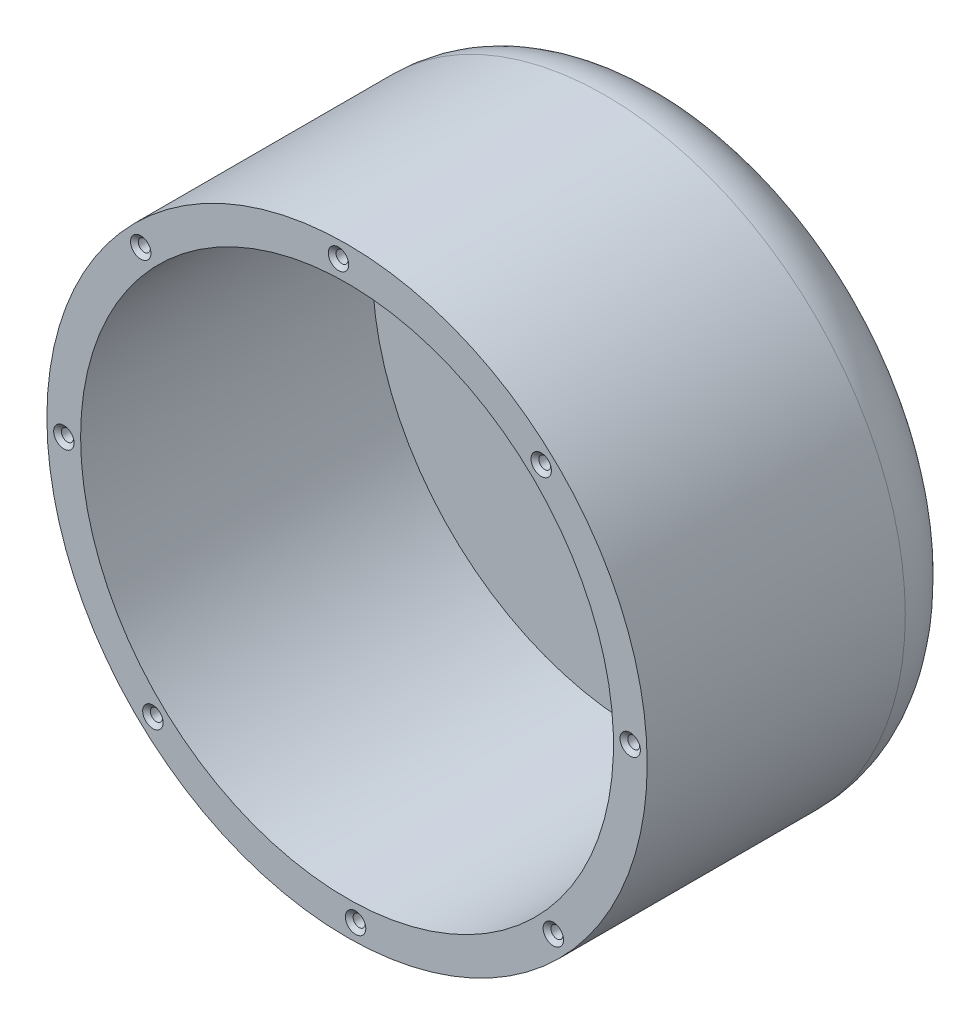
SolidWorks part; units mm, degrees
ref_plane "Front Plane" through (0, 0, 0) normal (0, 0, 1) x (1, 0, 0)
ref_plane "Top Plane" through (0, 0, 0) normal (0, 1, 0) x (1, 0, 0)
ref_plane "Right Plane" through (0, 0, 0) normal (1, 0, 0) x (0, 0, -1)
sketch "Sketch1" plane through (0, 0, 0) normal (0, 0, 1) x (1, 0, 0)
  circle A0 centre (0, 0) radius 44.5
  dimension "D1" = 89
extrude "Boss-Extrude1" add sketch "Sketch1" along normal mid plane 48.26
shell "Shell1" thickness 5
hole_wizard "CSK for #0 Flat Head Machine Screw (100)1" positions "3DSketch1" profile "Sketch5" countersink size "#0" standard "ANSI Inch"
sketch3d "3DSketch1"
  circle A0 centre (0, 0, 24.13) radius 39.5 construction
  point P0 (-1.2693, 41.9808, 24.13)
  point P7 (0, 0, 63.63)
  point P8 (65.1395, 21.7841, 0)
  dimension "D1" = 42
sketch "Sketch5" plane through (-1.2693, 41.9808, 24.13) normal (1, 0, 0) x (0, -1, 0)
  line L0 (0, 0) -> (0, 3.0742)
  line L1 (0, 3.0742) -> (0.889, 2.54)
  line L2 (0.889, 2.54) -> (0.889, 0.5222)
  line L3 (0.889, 0.5222) -> (1.5113, 0)
  line L5 (1.5113, 0) -> (0, 0)
  line L6 (-0.889, 0.5222) -> (-1.5113, 0) construction
  line L10 (0, 3.0742) -> (-0.889, 2.54) construction
  line L11 (0, -6.35) -> (0, 107.95) construction
  dimension "Hole Dia." = 1.778
  dimension "Hole Depth" = 2.54
  dimension "Near C'Sink Dia." = 3.0226
  dimension "Near C'Sink Angle" = 100
  dimension "Drill Angle" = 118
pattern_circular "CirPattern1" count 8 over 360 about axis through (0, 0, 0) along (0, 0, 1) of "CSK for #0 Flat Head Machine Screw (100)1"
fillet "Fillet1" radius 10 1 edges at (44.5, 0, -24.13)
